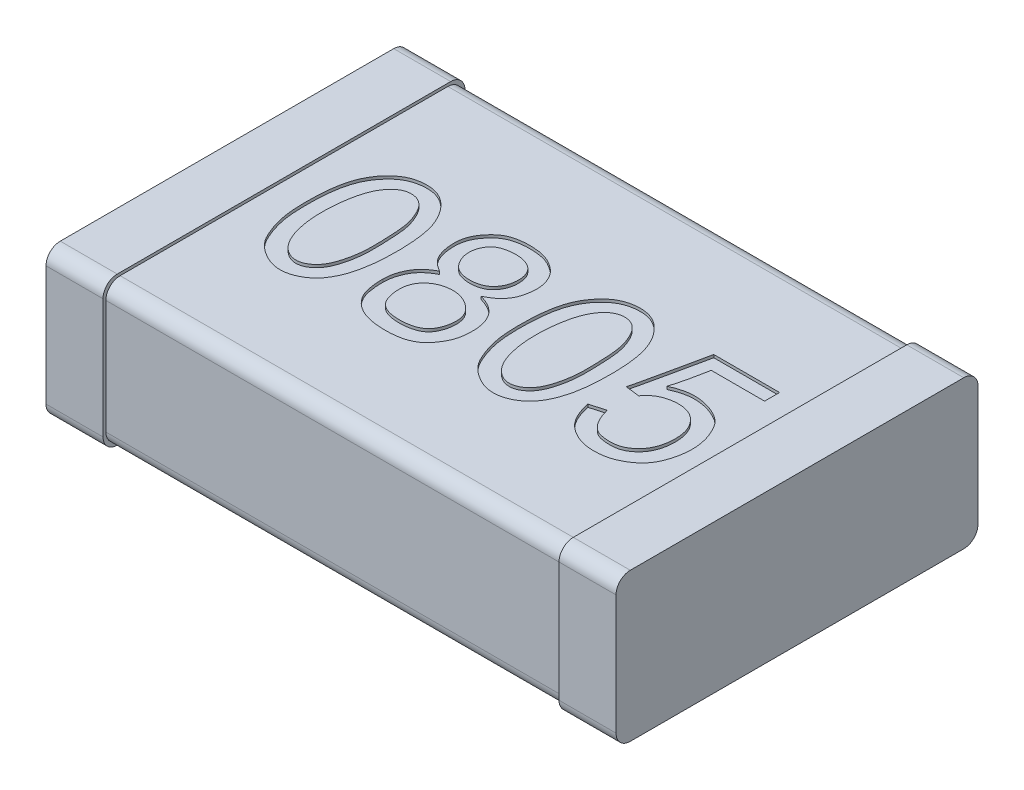
SolidWorks part; units mm, degrees
ref_plane "前视基准面" through (0, 0, 0) normal (0, 0, 1) x (1, 0, 0)
ref_plane "上视基准面" through (0, 0, 0) normal (0, 1, 0) x (1, 0, 0)
ref_plane "右视基准面" through (0, 0, 0) normal (1, 0, 0) x (0, 0, -1)
sketch "草图1" plane through (0, 0, 0) normal (0, 1, 0) x (1, 0, 0)
  line L0 (-31.3913, 0) -> (27.0565, 0) construction
  line L1 (0, 12.4242) -> (0, -8.2436) construction
  line L3 (-1, -0.625) -> (1, -0.625)
  line L4 (-1, -0.625) -> (-1, 0.625)
  line L5 (-1, 0.625) -> (1, 0.625)
  line L6 (1, -0.625) -> (1, 0.625)
  dimension "D1" = 2
  dimension "D2" = 1.25
extrude "凸台-拉伸1" add sketch "草图1" along normal blind 0.5
sketch "草图2" plane through (-1, 0, 0) normal (-1, 0, 0) x (0, 0, 1)
  line L0 (-0.7058, 0.25) -> (0.6827, 0.25) construction
  line L1 (0, -0.0713) -> (0, 0.602) construction
  line L2 (-0.625, 0.5) -> (0.625, 0.5) construction
  line L3 (-0.625, 0) -> (0.625, 0) construction
  line L5 (-0.635, 0.51) -> (0.635, 0.51)
  line L6 (-0.635, 0.51) -> (-0.635, -0.01)
  line L7 (-0.635, -0.01) -> (0.635, -0.01)
  line L8 (0.635, 0.51) -> (0.635, -0.01)
  dimension "D1" = 0.52
  dimension "D2" = 1.27
extrude "凸台-拉伸2" add sketch "草图2" against normal blind 0.2
sketch "草图3" plane through (1, 0, 0) normal (1, 0, 0) x (0, 0, -1)
  line L0 (-0.635, 0.51) -> (0.635, 0.51) construction
  line L1 (-0.635, -0.01) -> (-0.635, 0.51) construction
  line L2 (0.635, -0.01) -> (-0.635, -0.01) construction
  line L3 (0.635, 0.51) -> (0.635, -0.01) construction
  line L4 (-0.635, 0.51) -> (0.635, 0.51)
  line L5 (-0.635, -0.01) -> (-0.635, 0.51)
  line L6 (0.635, -0.01) -> (-0.635, -0.01)
  line L7 (0.635, 0.51) -> (0.635, -0.01)
extrude "凸台-拉伸3" add sketch "草图3" against normal blind 0.2
sketch "草图4" plane through (0, 0.5, 0) normal (0, 1, 0) x (1, 0, 0)
  text T0 "0805" font "黑体" height 0.5
extrude "切除-拉伸1" cut sketch "草图4" against normal blind 0.01
fillet "圆角1" radius 0.05 4 edges at (0, 0, 0.625) (0, 0, -0.625) (0, 0.5, -0.625) (0, 0.5, 0.625)
fillet "圆角2" radius 0.05 8 edges at (0.9, -0.01, 0.635) (0.9, -0.01, -0.635) (-0.9, -0.01, 0.635) (-0.9, -0.01, -0.635) (-0.9, 0.51, 0.635) (0.9, 0.51, 0.635) (0.9, 0.51, -0.635) (-0.9, 0.51, -0.635)
